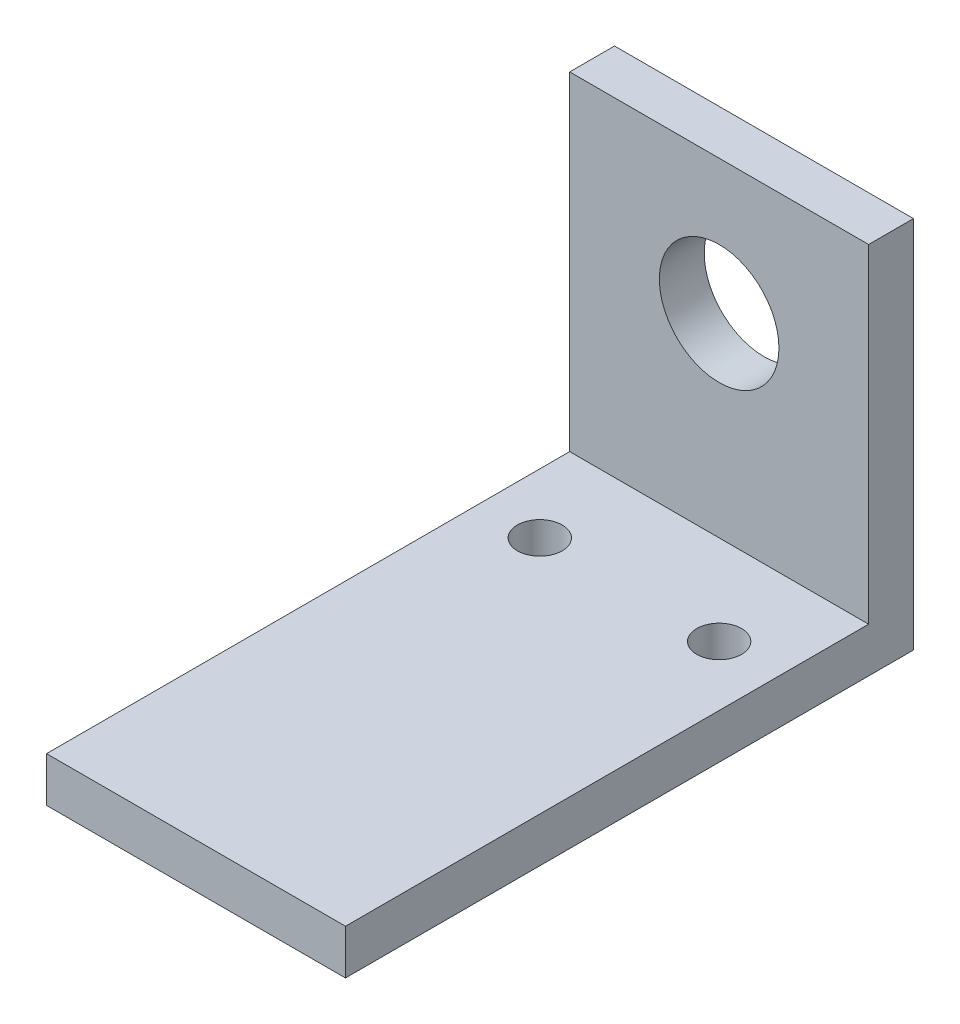
SolidWorks part; units mm, degrees
material "6063-O"
ref_plane "Front" through (0, 0, 0) normal (0, 0, 1) x (1, 0, 0)
ref_plane "Top" through (0, 0, 0) normal (0, 1, 0) x (1, 0, 0)
ref_plane "Right" through (0, 0, 0) normal (1, 0, 0) x (0, 0, -1)
sketch "草图1" plane through (0, 0, 0) normal (1, 0, 0) x (0, 0, -1)
  line L0 (0, 0) -> (0, 22)
  line L1 (0, 22) -> (3, 22)
  line L2 (3, 22) -> (3, -3)
  line L3 (3, -3) -> (-35, -3)
  line L4 (-35, -3) -> (-35, 0)
  line L5 (-35, 0) -> (0, 0)
  dimension "D1" = 22
  dimension "D2" = 3
  dimension "D3" = 25
  dimension "D4" = 38
extrude "凸台-拉伸1" add sketch "草图1" along normal blind 20
sketch "草图2" plane through (0, 0, 0) normal (0, 0, 1) x (1, 0, 0)
  line L0 (10, 22) -> (10, -3) construction
  line L1 (20, 22) -> (0, 22) construction
  line L2 (20, -3) -> (0, -3) construction
  circle A0 centre (10, 13) radius 4
  dimension "D1" = 8
  dimension "D2" = 9
extrude "切除-拉伸1" cut sketch "草图2" against normal up to next
sketch "草图3" plane through (0, 0, 0) normal (0, 1, 0) x (1, 0, 0)
  line L0 (10, 3) -> (10, -30.8482) construction
  line L1 (20, 3) -> (0, 3) construction
  circle A0 centre (4, -6) radius 1.5
  circle A1 centre (16, -6) radius 1.5
  dimension "D1" = 3
  dimension "D2" = 3
  dimension "D3" = 12
  dimension "D4" = 9
extrude "切除-拉伸2" cut sketch "草图3" against normal up to next
